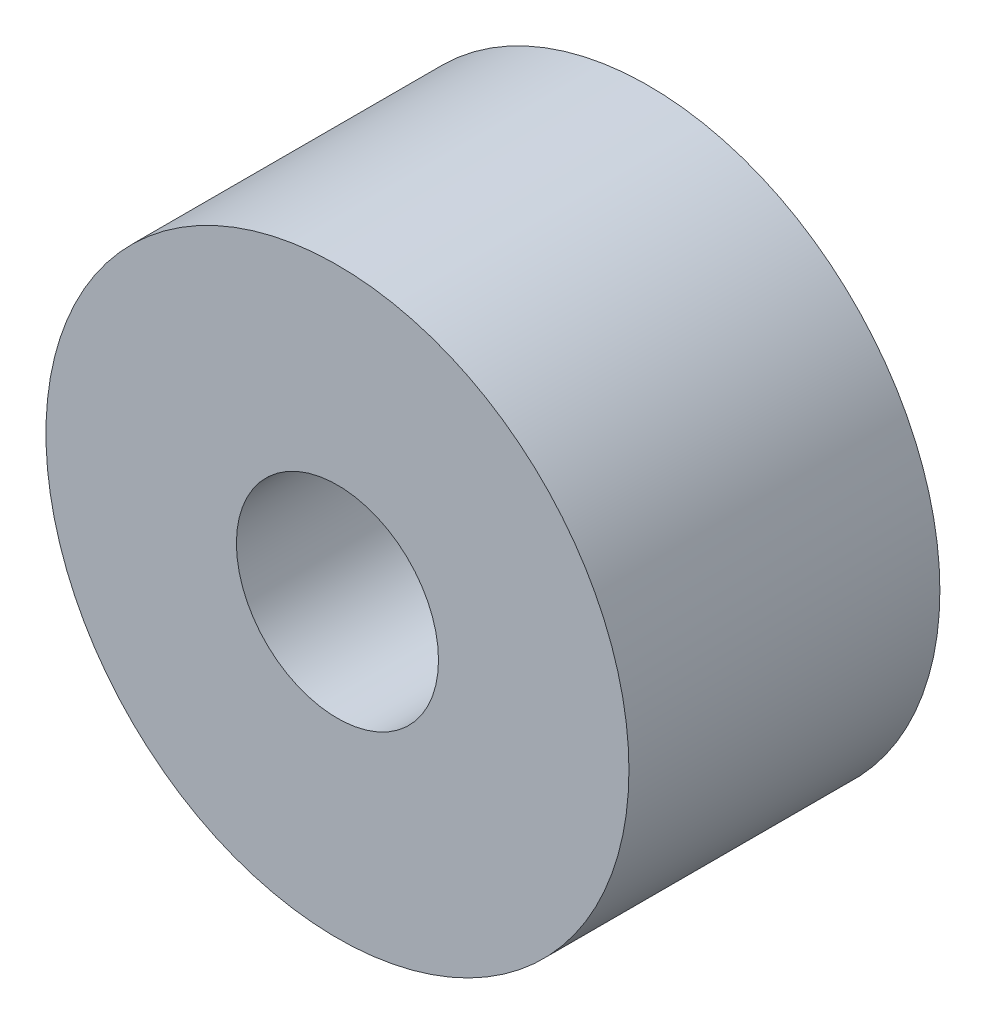
SolidWorks part; units mm, degrees
ref_plane "前视基准面" through (0, 0, 0) normal (0, 0, 1) x (1, 0, 0)
ref_plane "上视基准面" through (0, 0, 0) normal (0, 1, 0) x (1, 0, 0)
ref_plane "右视基准面" through (0, 0, 0) normal (1, 0, 0) x (0, 0, -1)
sketch "草图1" plane through (0, 0, 0) normal (0, 0, 1) x (1, 0, 0)
  circle A0 centre (0, 0) radius 2.6
  circle A1 centre (0, 0) radius 7.5
  dimension "D1" = 5.2
  dimension "D2" = 15
extrude "凸台-拉伸1" add sketch "草图1" along normal blind 8
